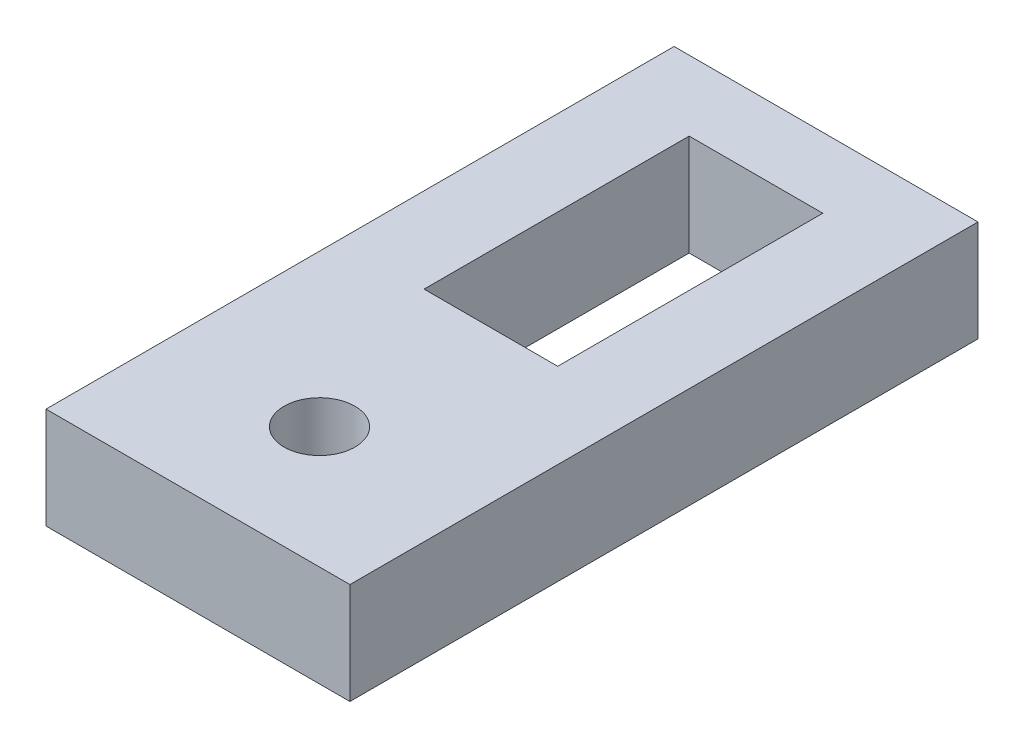
SolidWorks part; units mm, degrees
ref_plane "前视基准面" through (0, 0, 0) normal (0, 0, 1) x (1, 0, 0)
ref_plane "上视基准面" through (0, 0, 0) normal (0, 1, 0) x (1, 0, 0)
ref_plane "右视基准面" through (0, 0, 0) normal (1, 0, 0) x (0, 0, -1)
sketch "草图1" plane through (0, 0, 0) normal (1, 0, 0) x (0, 0, -1)
  line L1 (50, -5) -> (-12, -5)
  line L2 (50, -5) -> (50, 5)
  line L3 (50, 5) -> (-12, 5)
  line L4 (-12, -5) -> (-12, 5)
  line L5 (50, -5) -> (-12, 5) construction
  line L6 (50, 5) -> (-12, -5) construction
  point P0 (19, 0)
  point P5 (0, 0)
  point P6 (0, 0)
  point P7 (0, 0)
extrude "凸台-拉伸1" add sketch "草图1" along normal mid plane 30
sketch "草图2" plane through (0, -5, 0) normal (0, 1, 0) x (1, 0, 0)
  circle A0 centre (0, 0) radius 6.5
extrude "切除-拉伸1" cut sketch "草图2" along normal blind 5
sketch "草图4" plane through (0, 0, 0) normal (0, -1, 0) x (1, 0, 0)
  circle A0 centre (0, 0) radius 3.5
extrude "切除-拉伸3" cut sketch "草图4" against normal through all
sketch "草图3" plane through (0, 5, 0) normal (0, 1, 0) x (1, 0, 0)
  line L1 (6.5957, 43.0832) -> (-6.5957, 43.0832)
  line L2 (6.5957, 43.0832) -> (6.5957, 16.9168)
  line L3 (6.5957, 16.9168) -> (-6.5957, 16.9168)
  line L4 (-6.5957, 43.0832) -> (-6.5957, 16.9168)
  line L5 (6.5957, 43.0832) -> (-6.5957, 16.9168) construction
  line L6 (6.5957, 16.9168) -> (-6.5957, 43.0832) construction
  point P0 (0, 30)
  point P5 (0, 0)
extrude "切除-拉伸2" cut sketch "草图3" against normal through all
